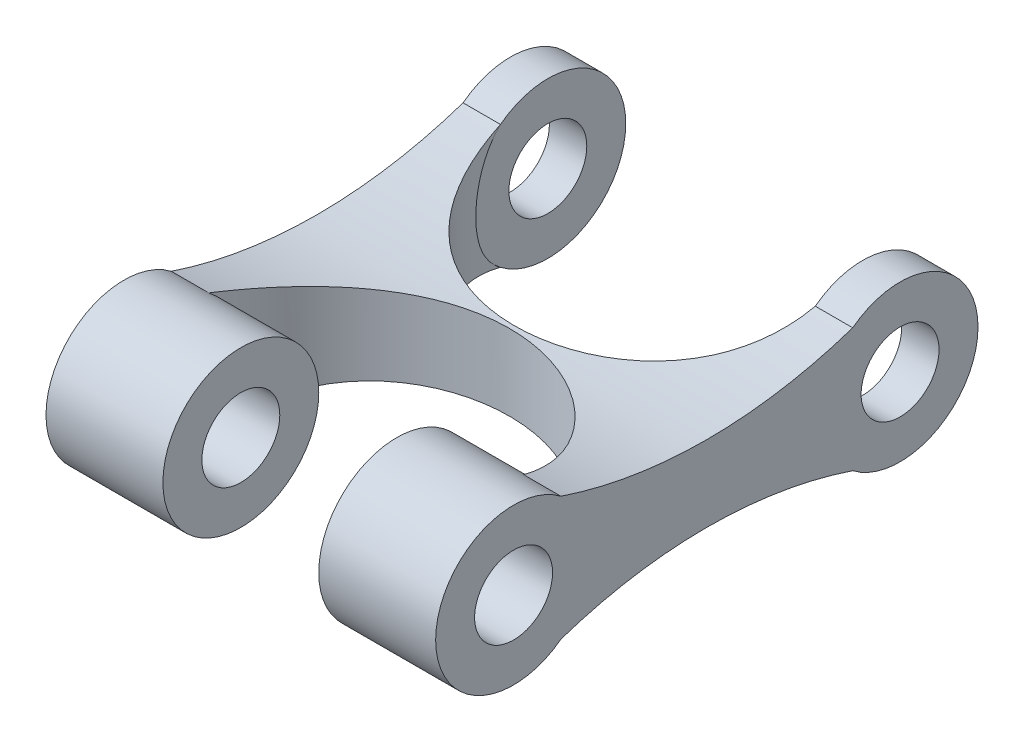
SolidWorks part; units mm, degrees
ref_plane "Front Plane" through (0, 0, 0) normal (0, 0, 1) x (1, 0, 0)
ref_plane "Top Plane" through (0, 0, 0) normal (0, 1, 0) x (1, 0, 0)
ref_plane "Right Plane" through (0, 0, 0) normal (1, 0, 0) x (0, 0, -1)
sketch "Sketch2" plane through (0, 0, 0) normal (1, 0, 0) x (0, 0, -1)
  line L0 (-6.1991, 0) -> (6.1991, 0)
  circle A0 centre (6.1991, 0) radius 2.5
  circle A1 centre (-6.1991, 0) radius 2.5
  circle A2 centre (-6.1991, 0) radius 1.25
  circle A3 centre (6.1991, 0) radius 1.25
  point P3 (0, 0)
  dimension "D2" = 5
  dimension "D3" = 2.5
  dimension "D1" = 12.3982
extrude "Boss-Extrude1" add sketch "Sketch2" along normal mid plane 12.5
sketch "Sketch3" plane through (0, 0, 0) normal (1, 0, 0) x (0, 0, -1)
  circle A0 centre (6.1991, 0) radius 2.5 construction
  circle A1 centre (6.1991, 0) radius 1.25 construction
  circle A2 centre (-6.1991, 0) radius 1.25 construction
  circle A3 centre (-6.1991, 0) radius 2.5 construction
  circle A4 centre (6.1991, 0) radius 2.5
  circle A5 centre (6.1991, 0) radius 1.25
  circle A6 centre (-6.1991, 0) radius 1.25
  circle A7 centre (-6.1991, 0) radius 2.5
extrude "Cut-Extrude1" cut sketch "Sketch3" against normal mid plane 10.1
sketch "Sketch4" plane through (0, 0, 0) normal (1, 0, 0) x (0, 0, -1)
  line L0 (-5.2366, 0) -> (3.6991, 0) construction
  circle A0 centre (6.1991, 0) radius 2.5 construction
  circle A1 centre (-6.1991, 0) radius 2.5 construction
  arc A2 (4.6799, 1.9854) -> (4.6799, -1.9854) centre (6.1991, 0) ccw
  arc A3 (-4.6799, -1.9854) -> (-4.6799, 1.9854) centre (-6.1991, 0) ccw
  arc A4 (-4.6799, 1.9854) -> (4.6799, 1.9854) centre (0, 15.8881) ccw
  arc A5 (-4.6799, -1.9854) -> (4.6799, -1.9854) centre (0, -15.8881) cw
extrude "Boss-Extrude2" add sketch "Sketch4" along normal mid plane 12.5
sketch "Sketch5" plane through (0, 0, 0) normal (0, 1, 0) x (1, 0, 0)
  line L0 (-5.05, 4.6799) -> (5.05, 4.6799)
  line L5 (5.05, -4.6799) -> (-5.05, -4.6799)
  arc A0 (-5.05, 4.6799) -> (5.05, 4.6799) centre (0, 5.1478) ccw
  arc A1 (-5.05, -4.6799) -> (5.05, -4.6799) centre (0, -5.1478) cw
  point P0 (0, 0)
extrude "Cut-Extrude2" cut sketch "Sketch5" against normal through all both and the other way through all contours L0 A0 | L5 A1
sketch "Sketch6" plane through (-5.05, 0, 0) normal (1, 0, 0) x (0, 0, -1)
  circle A0 centre (-6.1991, 0) radius 1.25 construction
  circle A1 centre (-6.1991, 0) radius 1.25
  arc A2 (-4.6799, 1.9854) -> (-4.6799, -1.9854) centre (-6.1991, 0) ccw
  arc A3 (-4.6799, -1.9854) -> (-4.6799, 1.9854) centre (-6.1991, 0) ccw
  arc A4 (-4.6799, 1.9854) -> (-4.6799, -1.9854) centre (-6.1991, 0) ccw
  arc A5 (-4.6799, -1.9854) -> (-4.6799, 1.9854) centre (-6.1991, 0) ccw
  dimension "D1" = 0
extrude "Boss-Extrude3" add sketch "Sketch6" along normal blind 11.001
sketch "Sketch7" plane through (0, 0, 0) normal (1, 0, 0) x (0, 0, -1)
  circle A2 centre (-6.1991, 0) radius 2.5
  circle A5 centre (-6.1991, 0) radius 1.25
extrude "Cut-Extrude3" cut sketch "Sketch7" against normal mid plane 5
scale "Scale1" scale about centroid uniform scaling yes scale factor 1.5
